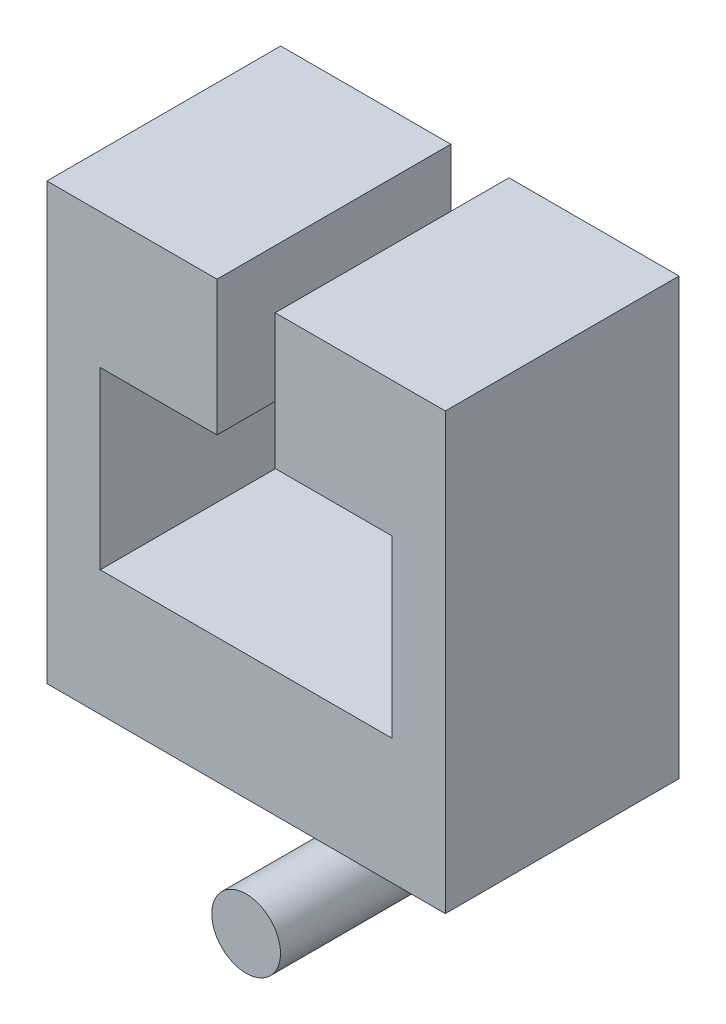
SolidWorks part; units mm, degrees
material "6061-T6 (SS)"
ref_plane "Front Plane" through (0, 0, 0) normal (0, 0, 1) x (1, 0, 0)
ref_plane "Top Plane" through (0, 0, 0) normal (0, 1, 0) x (1, 0, 0)
ref_plane "Right Plane" through (0, 0, 0) normal (1, 0, 0) x (0, 0, -1)
sketch "Sketch1" plane through (0, 0, 0) normal (0, 0, 1) x (1, 0, 0)
  circle A0 centre (0, 0) radius 7.4727
  dimension "D1" = 14.9454
extrude "Boss-Extrude1" add sketch "Sketch1" against normal blind 50.8
sketch "Sketch2" plane through (0, 0, -50.8) normal (0, 0, -1) x (-1, 0, 0)
  line L0 (-11.8069, 0) -> (11.7465, 0) construction
  line L1 (-7.4727, 0) -> (7.4727, 0)
  line L2 (-7.4727, 0) -> (-7.4727, 25.4)
  line L3 (7.4727, 0) -> (7.4727, 25.4)
  line L4 (-7.4727, 25.4) -> (7.4727, 25.4)
  circle A0 centre (0, 0) radius 7.4727 construction
  dimension "D1" = 25.4
extrude "Boss-Extrude2" add sketch "Sketch2" against normal blind 12.9515
sketch "Sketch3" plane through (0, 0, -50.8) normal (0, 0, -1) x (-1, 0, 0)
  line L0 (0, 25.4) -> (0, 42.7992) construction
  line L1 (7.4727, 25.4) -> (-7.4727, 25.4) construction
  line L3 (-31.7043, 25.4) -> (31.7043, 25.4)
  line L4 (-31.7043, 25.4) -> (-31.7043, 52.6186)
  line L5 (-31.7043, 52.6186) -> (31.7043, 52.6186)
  line L6 (31.7043, 25.4) -> (31.7043, 52.6186)
  point P9 (0, 52.6186)
  dimension "D1" = 27.2186
  dimension "D2" = 63.4086
extrude "Boss-Extrude3" add sketch "Sketch3" against normal blind 50.8
sketch "Sketch5" plane through (0, 0, -50.8) normal (0, 0, -1) x (-1, 0, 0)
  line L0 (0, 52.6186) -> (0, 98.0209) construction
  line L1 (-31.7043, 52.6186) -> (-43.2867, 52.6186)
  line L2 (-31.7043, 52.6186) -> (-31.7043, 90.6932)
  line L3 (-31.7043, 90.6932) -> (-43.2867, 90.6932)
  line L4 (-43.2867, 52.6186) -> (-43.2867, 90.6932)
  line L5 (31.7043, 52.6186) -> (-31.7043, 52.6186) construction
  line L6 (31.7043, 90.6932) -> (43.2867, 90.6932)
  line L7 (43.2867, 52.6186) -> (43.2867, 90.6932)
  line L8 (31.7043, 52.6186) -> (43.2867, 52.6186)
  line L9 (31.7043, 52.6186) -> (31.7043, 90.6932)
  dimension "D1" = 11.5824
  dimension "D2" = 38.0746
extrude "Boss-Extrude4" add sketch "Sketch5" against normal blind 50.8
sketch "Sketch7" plane through (0, 0, -50.8) normal (0, 0, -1) x (-1, 0, 0)
  line L0 (0, 52.6186) -> (0, -12.1187) construction
  line L1 (-31.7043, 25.4) -> (-43.2867, 25.4)
  line L2 (-31.7043, 25.4) -> (-31.7043, 52.6186)
  line L3 (-31.7043, 52.6186) -> (-43.2867, 52.6186)
  line L4 (-43.2867, 25.4) -> (-43.2867, 52.6186)
  line L5 (31.7043, 52.6186) -> (-31.7043, 52.6186) construction
  line L6 (31.7043, 52.6186) -> (43.2867, 52.6186)
  line L7 (43.2867, 25.4) -> (43.2867, 52.6186)
  line L8 (31.7043, 25.4) -> (43.2867, 25.4)
  line L9 (31.7043, 25.4) -> (31.7043, 52.6186)
extrude "Boss-Extrude5" add sketch "Sketch7" against normal blind 50.8
sketch "Sketch8" plane through (0, 0, -50.8) normal (0, 0, -1) x (-1, 0, 0)
  line L0 (0, 52.6186) -> (0, 127.0784) construction
  line L1 (-31.7043, 90.6932) -> (-6.3246, 90.6932)
  line L2 (-31.7043, 90.6932) -> (-31.7043, 120.0074)
  line L3 (-31.7043, 120.0074) -> (-6.3246, 120.0074)
  line L4 (-6.3246, 90.6932) -> (-6.3246, 120.0074)
  line L5 (31.7043, 52.6186) -> (-31.7043, 52.6186) construction
  line L6 (31.7043, 120.0074) -> (6.3246, 120.0074)
  line L7 (6.3246, 90.6932) -> (6.3246, 120.0074)
  line L8 (31.7043, 90.6932) -> (6.3246, 90.6932)
  line L9 (31.7043, 90.6932) -> (31.7043, 120.0074)
  dimension "D1" = 25.3797
  dimension "D2" = 29.3141
extrude "Boss-Extrude6" add sketch "Sketch8" against normal blind 50.8 separate body
sketch "Sketch9" plane through (0, 0, -50.8) normal (0, 0, -1) x (-1, 0, 0)
  line L0 (-31.7043, 120.0074) -> (-49.4517, 120.0074) construction
  line L1 (-43.2867, 90.6932) -> (-43.2867, 123.6577) construction
  line L2 (0, 52.6186) -> (0, 128.337) construction
  line L3 (-31.7043, 90.6932) -> (-43.2867, 90.6932)
  line L4 (-31.7043, 90.6932) -> (-31.7043, 120.0074)
  line L5 (-31.7043, 120.0074) -> (-43.2867, 120.0074)
  line L6 (-43.2867, 90.6932) -> (-43.2867, 120.0074)
  line L7 (31.7043, 52.6186) -> (-31.7043, 52.6186) construction
  line L8 (31.7043, 120.0074) -> (43.2867, 120.0074)
  line L9 (43.2867, 90.6932) -> (43.2867, 120.0074)
  line L10 (31.7043, 90.6932) -> (43.2867, 90.6932)
  line L11 (31.7043, 90.6932) -> (31.7043, 120.0074)
extrude "Boss-Extrude7" add sketch "Sketch9" against normal blind 50.8
sketch "Sketch10" plane through (-7.4727, 0, 0) normal (-1, 0, 0) x (0, 0, 1)
  line L0 (-37.8485, 0) -> (-12.4485, 25.4)
  line L1 (0, 25.4) -> (-50.8, 25.4) construction
  line L2 (-12.4485, 25.4) -> (-37.8485, 25.4)
  line L3 (-37.8485, 25.4) -> (-37.8485, 0)
  dimension "D1" = 25.4
extrude "Boss-Extrude8" add sketch "Sketch10" against normal blind 2.54
sketch "Sketch11" plane through (7.4727, 0, 0) normal (1, 0, 0) x (0, 0, -1)
  line L0 (37.8485, 0) -> (12.4485, 25.4)
  line L1 (0, 25.4) -> (50.8, 25.4) construction
  line L2 (12.4485, 25.4) -> (37.8485, 25.4)
  line L3 (37.8485, 25.4) -> (37.8485, 5.6133) construction
  line L4 (37.8485, 25.4) -> (37.8485, 0)
  dimension "D1" = 25.4
extrude "Boss-Extrude9" add sketch "Sketch11" against normal blind 2.54
equation "\"SF\"= 4'Safety Factor"
equation "\"Tmax\"= 30000'Max Shear Stress (psi)"
equation "\"Max Stress\"= 40000'Max Normal Stress (psi)"
equation "\"F\"= 600'Force (lbF)"
equation "\"l1\"= 2'Length of Feature 1 (in)"
equation "\"r1\"= ( 4 * ( \"SF\" * 2 * \"F\" * \"l1\" ) / ( 2 * \"Tmax\" * PI ) ) ^ ( 1 / 3 )'Radius of Feature 1 (in)"
equation "\"b2\" = 5 * ( \"SF\" * 2 * \"F\" ) / ( \"Max Stress\" * 2 * \"r1\" )'Base of Feature 2 (in)"
equation "\"E\"= 10000'Young's Modulus (ksi)"
equation "\"disp\"= 0.005'Displacement (in)"
equation "\"w2\"= ( ( \"SF\" * 64 * 2 * \"F\" * ( \"l1\" ^ 3 ) ) / ( 3 * PI * \"E\" * 10 ^ 3 * \"disp\" ) ) ^ ( 1 / 4 )'Width of Feature 2 (in)"
equation "\"l2\"= 1'Length of Feature 2 (in)"
equation "\"b3\"= 2.4964'Base of Feature 3 (in)"
equation "\"l3\"= 2'Length of Feature 3 (in)"
equation "\"h3\"= ( ( 4 * \"SF\" * 2 * \"F\" * ( \"l3\" ^ 3 ) ) / ( \"E\" * 10 ^ 3 * \"b3\" * \"disp\" ) ) ^ ( 1 / 3 )'Height of Feature 3 (in)"
equation "\"l4\"= 2'Length of Feature 4 (in)"
equation "\"h4\"= 1.499'Height of Feature 4 (in)"
equation "\"b4\"= ( ( 4 * \"SF\" * \"F\" * ( \"l4\" ^ 3 ) ) / ( \"E\" * 10 ^ 3 * ( \"h4\" ^ 3 ) * \"disp\" ) )'Base of Feature 4 (in)"
equation "\"l5\"= \"l1\"'Length of Feature 5 (in)"
equation "\"b5\"= .9992'Base of Feature 5 (in)"
equation "\"h5\"= ( ( 4 * \"SF\" * \"F\" * ( \"l5\" ^ 3 ) ) / ( \"E\" * 10 ^ 3 * \"b5\" * \"disp\" ) ) ^ ( 1 / 3 )'Height of Feature 5 (in)"
